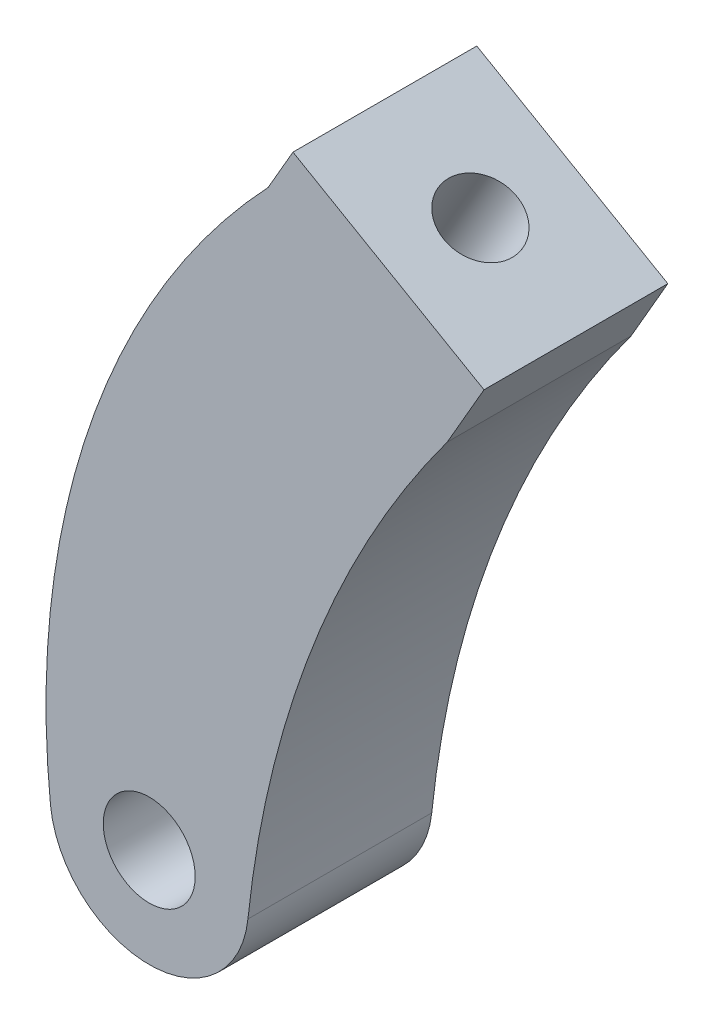
SolidWorks part; units mm, degrees
ref_plane "Plan de face" through (0, 0, 0) normal (0, 0, 1) x (1, 0, 0)
ref_plane "Plan de dessus" through (0, 0, 0) normal (0, 1, 0) x (1, 0, 0)
ref_plane "Plan de droite" through (0, 0, 0) normal (1, 0, 0) x (0, 0, -1)
sketch "Esquisse1" plane through (0, 0, 0) normal (0, 0, 1) x (1, 0, 0)
  line L0 (83.8692, -119.7148) -> (93.8692, -102.3943)
  line L1 (93.8692, -102.3943) -> (41.9076, -72.3943)
  line L2 (41.9076, -72.3943) -> (35.1517, -84.096)
  line L3 (29.6562, -259.1686) -> (-24.0485, -259.1686) construction
  circle A0 centre (2.8039, -256.3488) radius 12.5
  arc A1 (-24.0485, -259.1686) -> (29.6562, -259.1686) centre (2.8039, -256.3488) ccw
  arc A2 (35.1517, -84.096) -> (-24.0485, -259.1686) centre (196.0645, -236.0535) ccw
  arc A3 (29.6562, -259.1686) -> (83.8692, -119.7148) centre (312.5398, -288.8756) cw
  dimension "D2" = 25
  dimension "D3" = 27
  dimension "D4" = 30
  dimension "D5" = 20
  dimension "D1" = 60
extrude "Boss.-Extru.1" add sketch "Esquisse1" along normal mid plane 50
sketch "Esquisse3" plane through (0, 0, 0) normal (0, 0, 1) x (1, 0, 0)
  line L0 (67.8884, -87.3943) -> (50.3884, -117.7052)
  line L1 (93.8692, -102.3943) -> (41.9076, -72.3943) construction
  line L2 (50.3884, -117.7052) -> (44.6149, -107.7052)
  line L3 (44.6149, -107.7052) -> (59.2281, -82.3943)
  line L4 (59.2281, -82.3943) -> (67.8884, -87.3943)
  line L5 (67.8884, -87.3943) -> (66.4465, -87.0487)
  dimension "D1" = 60
  dimension "D2" = 10
  dimension "D3" = 35
revolve "Enlèvement de matière-Révolution1" cut sketch "Esquisse3" angle 360 about L0
